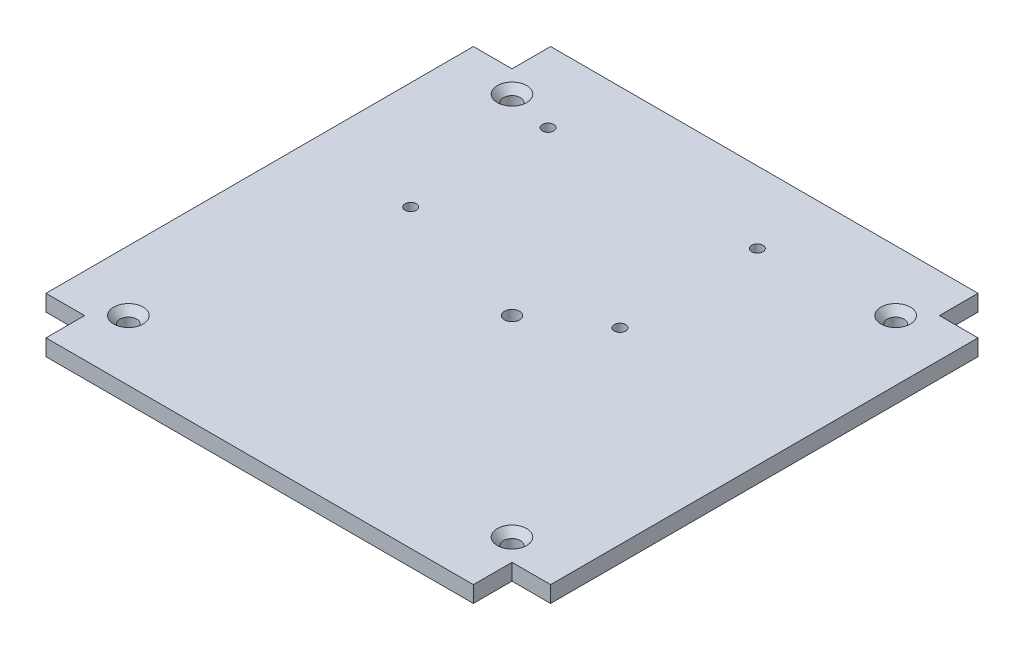
SolidWorks part; units mm, degrees
ref_plane "Front Plane" through (0, 0, 0) normal (0, 0, 1) x (1, 0, 0)
ref_plane "Top Plane" through (0, 0, 0) normal (0, 1, 0) x (1, 0, 0)
ref_plane "Right Plane" through (0, 0, 0) normal (1, 0, 0) x (0, 0, -1)
sketch "Sketch1" plane through (0, 0, 0) normal (0, 1, 0) x (1, 0, 0)
  line L1 (-49, -49) -> (49, -49)
  line L2 (-49, -49) -> (-49, 49)
  line L3 (-49, 49) -> (49, 49)
  line L4 (49, -49) -> (49, 49)
  line L5 (-49, -49) -> (49, 49) construction
  line L6 (-49, 49) -> (49, -49) construction
  point P0 (0, 0)
  dimension "D1" = 98
extrude "Boss-Extrude1" add sketch "Sketch1" along normal blind 3.175
sketch "Sketch2" plane through (0, 3.175, 0) normal (0, 1, 0) x (1, 0, 0)
  line L0 (41.5, 49) -> (49, 49)
  line L1 (-49, 49) -> (-41.5, 49)
  line L2 (-49, 49) -> (-49, 41.5)
  line L3 (-49, 41.5) -> (-41.5, 41.5)
  line L4 (-41.5, 49) -> (-41.5, 41.5)
  line L5 (41.5, 49) -> (41.5, 41.5)
  line L6 (41.5, 41.5) -> (49, 41.5)
  line L7 (49, 49) -> (49, 41.5)
  line L8 (41.5, -41.5) -> (49, -41.5)
  line L9 (41.5, -41.5) -> (41.5, -49)
  line L10 (41.5, -49) -> (49, -49)
  line L11 (49, -41.5) -> (49, -49)
  line L12 (-49, -41.5) -> (-41.5, -41.5)
  line L13 (-49, -41.5) -> (-49, -49)
  line L14 (-49, -49) -> (-41.5, -49)
  line L15 (-41.5, -41.5) -> (-41.5, -49)
  line L16 (49, -49) -> (49, 49) construction
  line L17 (-49, -49) -> (49, -49) construction
  line L18 (49, 49) -> (-49, 49) construction
  dimension "D1" = 7.5
  dimension "D2" = 2
  dimension "D3" = 2
extrude "Cut-Extrude1" cut sketch "Sketch2" against normal through all
hole_wizard "#4 Clearance Hole1" positions "Sketch5" profile "Sketch4" hole size "#4" standard "ANSI Inch" end condition through all
sketch "Sketch5" plane through (0, 3.175, 0) normal (0, 1, 0) x (1, 0, 0)
  point P0 (0, 0)
sketch "Sketch4" plane through (0, 3.175, 0) normal (1, 0, 0) x (0, 0, 1)
  line L0 (0, 0) -> (0, 3.175)
  line L1 (0, 3.175) -> (1.4732, 3.175)
  line L2 (1.4732, 3.175) -> (1.4732, 0)
  line L5 (1.4732, 0) -> (0, 0)
  line L11 (0, -6.35) -> (0, 107.95) construction
  dimension "Thru Hole Dia." = 2.9464
  dimension "Thru Hole Depth" = 3.175
hole_wizard "M2 Clearance Hole1" positions "Sketch8" profile "Sketch7" hole size "M2" standard "ISO" end condition through all
sketch "Sketch8" plane through (0, 3.175, 0) normal (0, 1, 0) x (1, 0, 0)
  line L1 (-28.095, 35.095) -> (12.545, 35.095) construction
  line L2 (-28.095, 35.095) -> (-28.095, 8.425) construction
  line L3 (-28.095, 8.425) -> (12.545, 8.425) construction
  line L4 (12.545, 35.095) -> (12.545, 8.425) construction
  line L6 (-30, 37) -> (14.45, 37) construction
  line L7 (-30, 37) -> (-30, 6.52) construction
  line L8 (-30, 6.52) -> (14.45, 6.52) construction
  line L9 (14.45, 37) -> (14.45, 6.52) construction
  line L10 (-30, 37) -> (-28.095, 35.095) construction
  line L11 (-28.095, 8.425) -> (-30, 6.52) construction
  line L12 (12.545, 35.095) -> (14.45, 37) construction
  line L13 (12.545, 8.425) -> (14.45, 6.52) construction
  line L17 (14.45, 28.11) -> (41.12, 28.11) construction
  line L18 (14.45, 28.11) -> (14.45, 15.41) construction
  line L19 (14.45, 15.41) -> (41.12, 15.41) construction
  line L20 (41.12, 28.11) -> (41.12, 15.41) construction
  line L21 (-30, 21.76) -> (41.12, 21.76) construction
  line L22 (-49, 41.5) -> (-49, -41.5) construction
  line L23 (41.5, 49) -> (-41.5, 49) construction
  point P0 (-28.095, 35.095)
  point P7 (12.545, 35.095)
  point P8 (12.545, 8.425)
  point P9 (-28.095, 8.425)
  dimension "D3" = 26.67
  dimension "D4" = 40.64
  dimension "D5" = 44.45
  dimension "D6" = 30.48
  dimension "D7" = 19
  dimension "D8" = 12
  dimension "D9" = 12.7
  dimension "D10" = 26.67
  dimension "D1" = 2
  dimension "D2" = 2
sketch "Sketch7" plane through (-28.095, 3.175, -35.095) normal (1, 0, 0) x (0, 0, 1)
  line L0 (0, 0) -> (0, 3.175)
  line L1 (0, 3.175) -> (1.1, 3.175)
  line L2 (1.1, 3.175) -> (1.1, 0)
  line L5 (1.1, 0) -> (0, 0)
  line L11 (0, -6.35) -> (0, 107.95) construction
  dimension "Thru Hole Dia." = 2.2
  dimension "Thru Hole Depth" = 3.175
hole_wizard "CSK for #4 Flat Head Machine Screw1" positions "Sketch10" profile "Sketch9" countersink size "#4" standard "ANSI Inch" end condition through all
sketch "Sketch10" plane through (0, 3.175, 0) normal (0, 1, 0) x (1, 0, 0)
  circle A0 centre (37.25, -37.25) radius 1.4732 construction
  circle A1 centre (37.25, 37.25) radius 1.4732 construction
  circle A2 centre (-37.25, 37.25) radius 1.4732 construction
  circle A3 centre (-37.25, -37.25) radius 1.4732 construction
  point P0 (37.25, -37.25)
  point P2 (-37.25, -37.25)
  point P4 (-37.25, 37.25)
  point P6 (37.25, 37.25)
sketch "Sketch9" plane through (37.25, 3.175, 37.25) normal (1, 0, 0) x (0, 0, 1)
  line L0 (0, 0) -> (0, 3.175)
  line L1 (0, 3.175) -> (1.6319, 3.175)
  line L2 (1.6319, 3.175) -> (1.6319, 1.4098)
  line L3 (1.6319, 1.4098) -> (2.8575, 0)
  line L5 (2.8575, 0) -> (0, 0)
  line L6 (-1.6319, 1.4098) -> (-2.8575, 0) construction
  line L11 (0, -6.35) -> (0, 107.95) construction
  dimension "Thru Hole Dia." = 3.2639
  dimension "Thru Hole Depth" = 3.175
  dimension "Near C'Sink Dia." = 5.715
  dimension "Near C'Sink Angle" = 82
